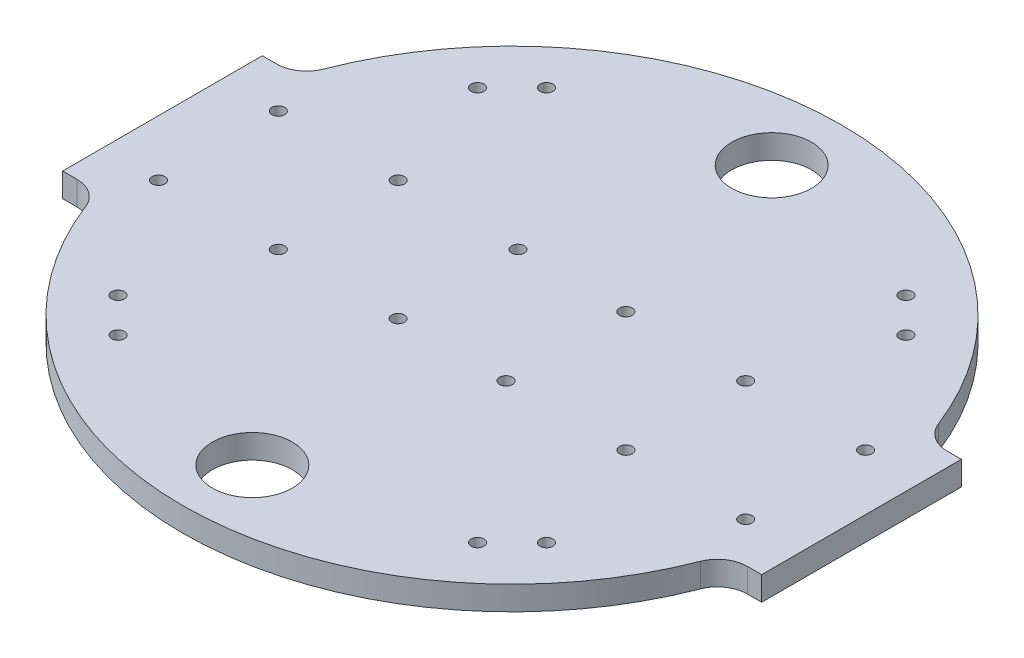
SolidWorks part; units mm, degrees
ref_plane "Plan de face" through (0, 0, 0) normal (0, 0, 1) x (1, 0, 0)
ref_plane "Plan de dessus" through (0, 0, 0) normal (0, 1, 0) x (1, 0, 0)
ref_plane "Plan de droite" through (0, 0, 0) normal (1, 0, 0) x (0, 0, -1)
sketch "Esquisse1" plane through (0, 0, 0) normal (0, 1, 0) x (1, 0, 0)
  line L0 (-87.5, 25) -> (-78.6209, 25)
  line L1 (-87.5, 0) -> (87.5, 0) construction
  line L2 (-87.5, -25) -> (87.5, -25) construction
  line L3 (-87.5, -25) -> (-87.5, 25)
  line L4 (0, 82.5) -> (0, -82.5) construction
  line L5 (-87.5, 25) -> (87.5, 25) construction
  line L6 (87.5, -25) -> (87.5, 25)
  line L7 (-87.5, -25) -> (-78.6209, -25)
  line L8 (87.5, -25) -> (78.6209, -25)
  line L9 (87.5, 25) -> (78.6209, 25)
  line L10 (0, 0) -> (-53.6231, 44.9951) construction
  line L11 (0, 0) -> (-44.9951, 53.6231) construction
  circle A0 centre (0, 0) radius 82.5 construction
  arc A1 (78.6209, 25) -> (-78.6209, 25) centre (0, 0) ccw
  arc A2 (-78.6209, -25) -> (78.6209, -25) centre (0, 0) ccw
  circle A3 centre (0, 0) radius 70 construction
  circle A4 centre (-53.6231, 44.9951) radius 1.6
  circle A5 centre (-44.9951, 53.6231) radius 1.6
  circle A6 centre (53.6231, 44.9951) radius 1.6
  circle A7 centre (44.9951, 53.6231) radius 1.6
  circle A8 centre (44.9951, -53.6231) radius 1.6
  circle A9 centre (53.6231, -44.9951) radius 1.6
  circle A10 centre (-53.6231, -44.9951) radius 1.6
  circle A11 centre (-44.9951, -53.6231) radius 1.6
  circle A12 centre (0, 65) radius 10
  circle A13 centre (0, -65) radius 10
  circle A14 centre (-73.5, 15) radius 1.6
  circle A15 centre (-73.5, -15) radius 1.6
  circle A16 centre (-43.5, 15) radius 1.6
  circle A17 centre (-43.5, -15) radius 1.6
  circle A18 centre (-13.5, 15) radius 1.6
  circle A19 centre (-13.5, -15) radius 1.6
  circle A20 centre (13.5, -15) radius 1.6
  circle A21 centre (13.5, 15) radius 1.6
  circle A22 centre (43.5, 15) radius 1.6
  circle A23 centre (43.5, -15) radius 1.6
  circle A24 centre (73.5, -15) radius 1.6
  circle A25 centre (73.5, 15) radius 1.6
  point P35 (0, 0)
  dimension "D1" = 165
  dimension "D6" = 10
  dimension "D5" = 40
  dimension "D8" = 65
  dimension "D9" = 15
  dimension "D2" = 175
  dimension "D3" = 87.5
  dimension "D4" = 50
  dimension "D10" = 14
  dimension "D11" = 3
  dimension "D7" = 4
extrude "Boss.-Extru.1" add sketch "Esquisse1" along normal blind 6
fillet "Congé1" radius 7.5 4 edges at (-78.6209, 3, 25) (-78.6209, 3, -25) (78.6209, 3, -25) (78.6209, 3, 25)
